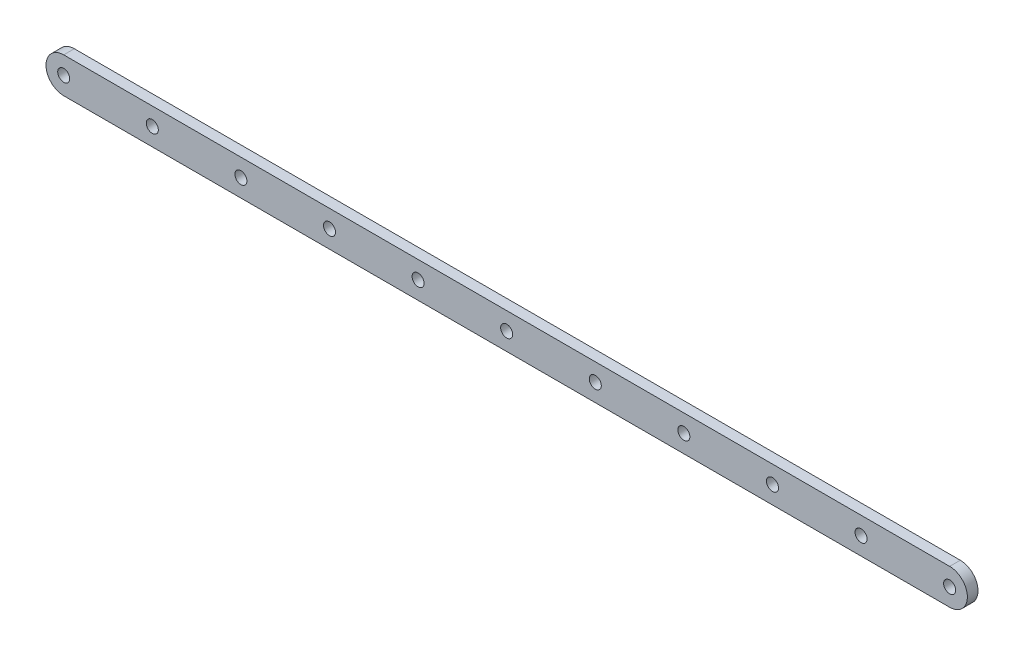
SolidWorks part; units mm, degrees
material "Pine"
ref_plane "Front Plane" through (0, 0, 0) normal (0, 0, 1) x (1, 0, 0)
ref_plane "Top Plane" through (0, 0, 0) normal (0, 1, 0) x (1, 0, 0)
ref_plane "Right Plane" through (0, 0, 0) normal (1, 0, 0) x (0, 0, -1)
sketch "Sketch1" plane through (0, 0, 0) normal (0, 0, 1) x (1, 0, 0)
  line L0 (0, 5) -> (250, 5)
  line L1 (250, -5) -> (0, -5)
  circle A0 centre (0, 0) radius 5
  circle A1 centre (250, 0) radius 5
  point P9 (300, 5)
  point P10 (300, -5)
  point P11 (0, 0)
  point P12 (0, -5)
  dimension "D1" = 250
  dimension "D2" = 10
extrude "Boss-Extrude1" add sketch "Sketch1" along normal blind 3 contours A1 L0 A0 L1 | A1 | A0
ref_plane "Plane1" through (0, 0, 1.5) normal (0, 0, 1) x (1, 0, 0)
sketch "Sketch2" plane through (0, 0, 3) normal (0, 0, 1) x (1, 0, 0)
  circle A0 centre (0, 0) radius 1.7
  circle A1 centre (250, 0) radius 1.7
  dimension "D1" = 3.4
extrude "Cut-Extrude1" cut sketch "Sketch2" against normal through all
pattern_linear "LPattern1" count 10 spacing 25 along (1, 0, 0) of "Cut-Extrude1"
